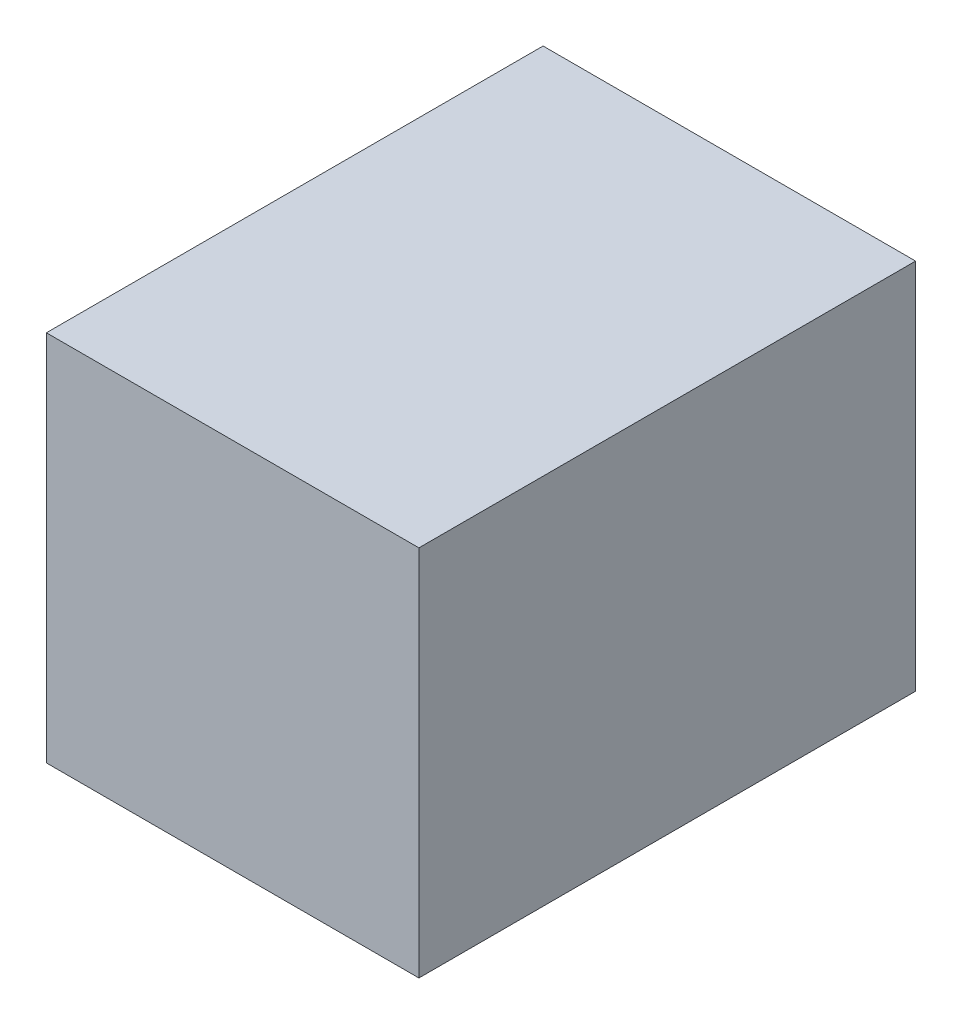
SolidWorks part; units mm, degrees
ref_plane "Front Plane" through (0, 0, 0) normal (0, 0, 1) x (1, 0, 0)
ref_plane "Top Plane" through (0, 0, 0) normal (0, 1, 0) x (1, 0, 0)
ref_plane "Right Plane" through (0, 0, 0) normal (1, 0, 0) x (0, 0, -1)
sketch "Sketch1" plane through (0, 0, 0) normal (0, 0, 1) x (1, 0, 0)
  line L1 (-3, 3) -> (3, 3)
  line L2 (-3, 3) -> (-3, -3)
  line L3 (-3, -3) -> (3, -3)
  line L4 (3, 3) -> (3, -3)
  line L5 (-3, 3) -> (3, -3) construction
  line L6 (-3, -3) -> (3, 3) construction
  point P0 (0, 0)
  dimension "D1" = 6
  dimension "D2" = 6
extrude "Boss-Extrude1" add sketch "Sketch1" along normal blind 8
